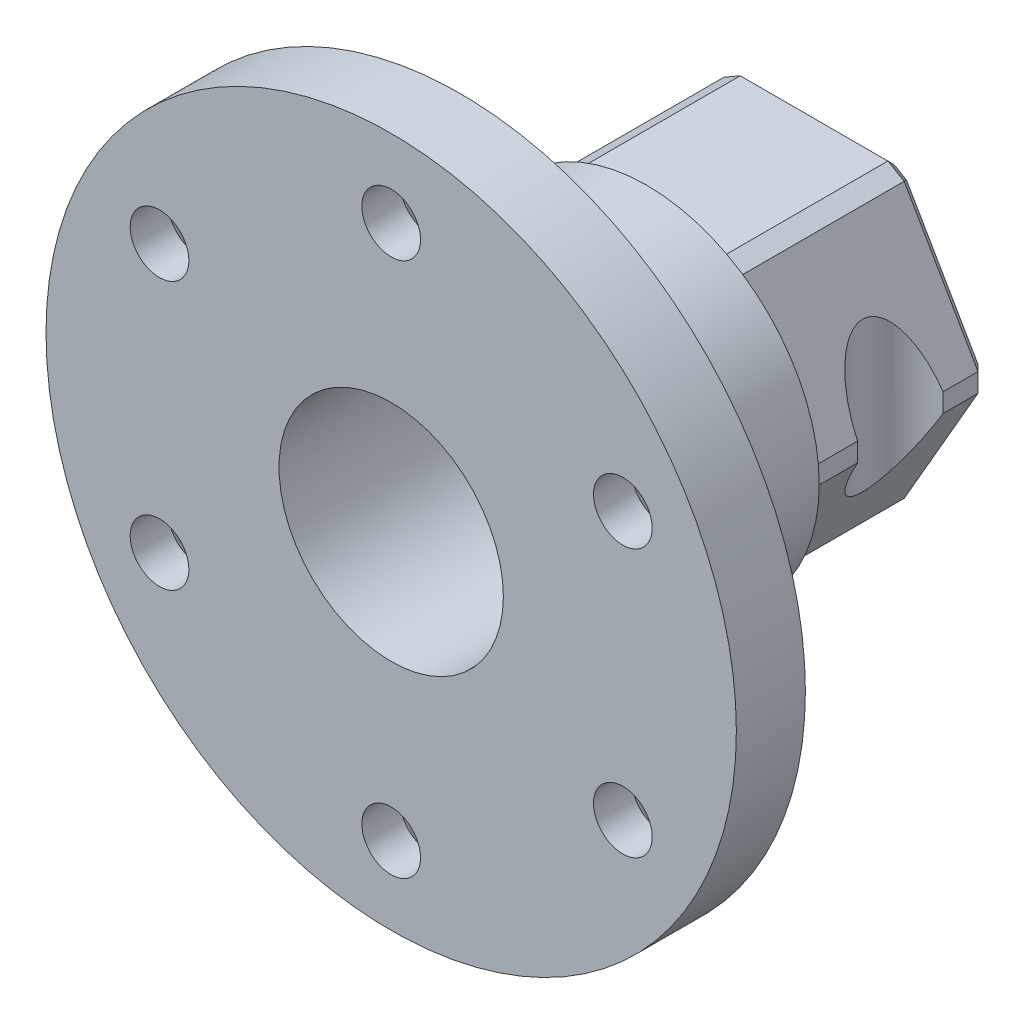
SolidWorks part; units mm, degrees
ref_plane "Front Plane" through (0, 0, 0) normal (0, 0, 1) x (1, 0, 0)
ref_plane "Top Plane" through (0, 0, 0) normal (0, 1, 0) x (1, 0, 0)
ref_plane "Right Plane" through (0, 0, 0) normal (1, 0, 0) x (0, 0, -1)
sketch "Sketch1" plane through (0, 0, 0) normal (0, 0, 1) x (1, 0, 0)
  line L1 (-4.9075, 8.5) -> (-9.815, 0)
  line L2 (-9.815, 0) -> (-4.9075, -8.5)
  line L3 (-4.9075, -8.5) -> (4.9075, -8.5)
  line L4 (4.9075, -8.5) -> (9.815, 0)
  line L5 (9.815, 0) -> (4.9075, 8.5)
  line L6 (4.9075, 8.5) -> (-4.9075, 8.5)
  circle A0 centre (0, 0) radius 8.5 construction
  dimension "D1" = 17
extrude "Boss-Extrude1" add sketch "Sketch1" along normal blind 10
sketch "Sketch2" plane through (0, 8.5, 0) normal (0, 1, 0) x (1, 0, 0)
  line L0 (-9.815, -10) -> (-9.815, 0) construction
  line L1 (9.815, -10) -> (9.815, 0) construction
  point P0 (-9.815, -5)
  point P4 (9.815, -5)
hole_wizard "Ø5.0mm Dowel Hole1" positions "Sketch2" profile "Sketch4" hole size "Ø5.0" standard "DIN" end condition through all
sketch "Sketch4" plane through (-9.815, 8.5, 5) normal (1, 0, 0) x (0, 0, 1)
  line L0 (0, 0) -> (0, 17)
  line L1 (0, 17) -> (2.5, 17)
  line L2 (2.5, 17) -> (2.5, 0.025)
  line L3 (2.5, 0.025) -> (2.525, 0)
  line L5 (2.525, 0) -> (0, 0)
  line L6 (-2.5, 0.025) -> (-2.525, 0) construction
  line L11 (0, -6.35) -> (0, 107.95) construction
  dimension "Thru Hole Dia." = 5
  dimension "Thru Hole Depth" = 17
  dimension "Near C'Sink Dia." = 5.05
  dimension "Near C'Sink Angle" = 90
sketch "Sketch5" plane through (0, 0, 10) normal (0, 0, 1) x (1, 0, 0)
  circle A0 centre (0, 0) radius 10
  dimension "D1" = 20
extrude "Boss-Extrude2" add sketch "Sketch5" along normal blind 10
sketch "Sketch6" plane through (0, 0, 20) normal (0, 0, 1) x (1, 0, 0)
  circle A0 centre (0, 0) radius 11.5
  dimension "D1" = 23
extrude "Boss-Extrude3" add sketch "Sketch6" along normal blind 1
sketch "Sketch7" plane through (0, 0, 21) normal (0, 0, 1) x (1, 0, 0)
  circle A0 centre (0, 0) radius 20
  dimension "D1" = 40
extrude "Boss-Extrude4" add sketch "Sketch7" along normal blind 4
sketch "Sketch8" plane through (0, 0, 21) normal (0, 0, -1) x (-1, 0, 0)
  circle A0 centre (0, 0) radius 11.5 construction
  point P0 (0, 15.5)
  point P8 (13.4234, 7.75)
  point P9 (13.4234, -7.75)
  point P10 (0, -15.5)
  point P11 (-13.4234, -7.75)
  point P12 (-13.4234, 7.75)
  dimension "D1" = 15.5
  dimension "D2" = 6
hole_wizard "CSK for M3 Hex Socket Countersunk Head Screw1" positions "Sketch8" profile "Sketch9" countersink size "M3" standard "DIN" end condition through all
sketch "Sketch9" plane through (0, 15.5, 21) normal (1, 0, 0) x (0, 1, 0)
  line L0 (0, 0) -> (0, 4)
  line L1 (0, 4) -> (1.7, 4)
  line L2 (1.7, 4) -> (1.7, 1.77)
  line L3 (1.7, 1.77) -> (3.47, 0)
  line L5 (3.47, 0) -> (0, 0)
  line L6 (-1.7, 1.77) -> (-3.47, 0) construction
  line L11 (0, -6.35) -> (0, 107.95) construction
  dimension "Thru Hole Dia." = 3.4
  dimension "Thru Hole Depth" = 4
  dimension "Near C'Sink Dia." = 6.94
  dimension "Near C'Sink Angle" = 90
sketch "Sketch10" plane through (0, 0, 25) normal (0, 0, 1) x (1, 0, 0)
  point P0 (0, 0)
hole_wizard "Ø13.0 (13) Diameter Hole1" positions "Sketch10" profile "Sketch11" hole size "Ø13.0" standard "DIN" end condition through all
sketch "Sketch11" plane through (0, 0, 25) normal (1, 0, 0) x (0, -1, 0)
  line L0 (0, 0) -> (0, 25)
  line L1 (0, 25) -> (6.5, 25)
  line L2 (6.5, 25) -> (6.5, 0)
  line L5 (6.5, 0) -> (0, 0)
  line L11 (0, -6.35) -> (0, 107.95) construction
  dimension "Thru Hole Dia." = 13
  dimension "Thru Hole Depth" = 25
sketch "Sketch12" plane through (0, 0, 10) normal (0, 0, -1) x (-1, 0, 0)
  line L6 (4.9075, 8.5) -> (-4.9075, 8.5)
  line L7 (-4.9075, 8.5) -> (-9.815, 0)
  line L8 (-9.815, 0) -> (-4.9075, -8.5)
  line L9 (-4.9075, -8.5) -> (4.9075, -8.5)
  line L10 (4.9075, -8.5) -> (9.815, 0)
  line L11 (9.815, 0) -> (4.9075, 8.5)
  line L12 (4.9075, 8.5) -> (-4.9075, 8.5)
  line L13 (-4.9075, 8.5) -> (-9.815, 0)
  line L14 (-9.815, 0) -> (-4.9075, -8.5)
  line L15 (-4.9075, -8.5) -> (4.9075, -8.5)
  line L16 (4.9075, -8.5) -> (9.815, 0)
  line L17 (9.815, 0) -> (4.9075, 8.5)
  circle A1 centre (0, 0) radius 10
  circle A2 centre (0, 0) radius 10
  dimension "D1" = 0
  dimension "D2" = 0
extrude "Cut-Extrude1" cut sketch "Sketch12" against normal blind 0.2
sketch "Sketch13" plane through (0, 0, 0) normal (0, 0, -1) x (-1, 0, 0)
  line L1 (0, 10.9697) -> (-9.5, 5.4848)
  line L2 (-9.5, 5.4848) -> (-9.5, -5.4848)
  line L3 (-9.5, -5.4848) -> (0, -10.9697)
  line L4 (0, -10.9697) -> (9.5, -5.4848)
  line L5 (9.5, -5.4848) -> (9.5, 5.4848)
  line L6 (9.5, 5.4848) -> (0, 10.9697)
  line L12 (4.9075, 8.5) -> (-4.9075, 8.5)
  line L13 (-4.9075, 8.5) -> (-9.815, 0)
  line L14 (-9.815, 0) -> (-4.9075, -8.5)
  line L15 (-4.9075, -8.5) -> (4.9075, -8.5)
  line L16 (4.9075, -8.5) -> (9.815, 0)
  line L17 (9.815, 0) -> (4.9075, 8.5)
  line L18 (4.9075, 8.5) -> (-4.9075, 8.5)
  line L19 (-4.9075, 8.5) -> (-9.815, 0)
  line L20 (-9.815, 0) -> (-4.9075, -8.5)
  line L21 (-4.9075, -8.5) -> (4.9075, -8.5)
  line L22 (4.9075, -8.5) -> (9.815, 0)
  line L23 (9.815, 0) -> (4.9075, 8.5)
  circle A0 centre (0, 0) radius 9.5 construction
  dimension "D1" = 19
  dimension "D2" = 0
extrude "Cut-Extrude2" cut sketch "Sketch13" against normal up to surface and the other way through all contours L1 L13 L14 | L6 A0 L13 | L5 L17 A0 | L4 L16 L17 | L3 L15 L16 | L2 L14 L15
chamfer "Chamfer1" distance 0.5 angle 45 13 edges at (7.3612, 4.25, 0) (4.75, 8.2272, 0) (0, 8.5, 0) (-4.75, 8.2272, 0) (-7.3612, 4.25, 0) (-9.5, 0, 0) (-7.3612, -4.25, 0) (-4.75, -8.2272, 0) (0, -8.5, 0) (4.75, -8.2272, 0) (7.3612, -4.25, 0) (9.5, 0, 0) (6.5, 0, 0)
